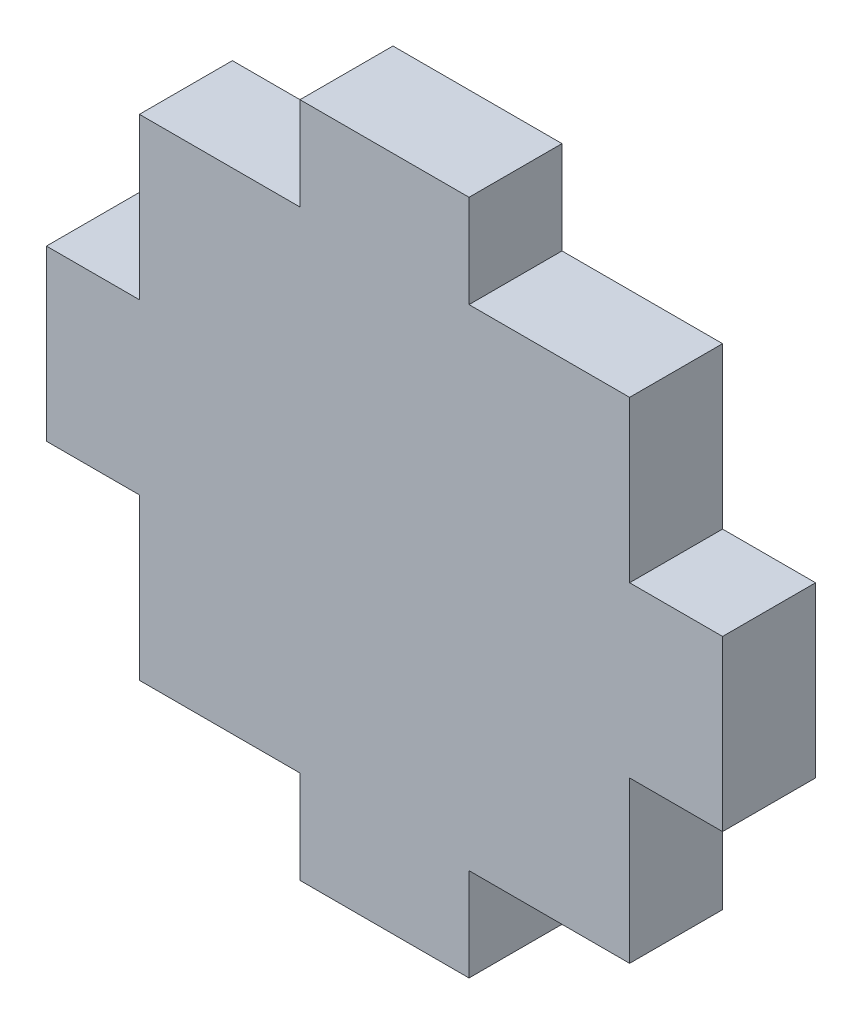
SolidWorks part; units mm, degrees
material "ﾁｰｸ材"
ref_plane "正面" through (0, 0, 0) normal (0, 0, 1) x (1, 0, 0)
ref_plane "平面" through (0, 0, 0) normal (0, 1, 0) x (1, 0, 0)
ref_plane "右側面" through (0, 0, 0) normal (1, 0, 0) x (0, 0, -1)
sketch "ｽｹｯﾁ1" plane through (0, 0, 0) normal (0, 0, 1) x (1, 0, 0)
  line L0 (-5, 14.5) -> (-14.5, 14.5)
  line L1 (14.5, 14.5) -> (5, 14.5)
  line L2 (14.5, 14.5) -> (14.5, 5)
  line L3 (14.5, -14.5) -> (5, -14.5)
  line L4 (-14.5, 14.5) -> (-14.5, 5)
  line L5 (14.5, 14.5) -> (-14.5, -14.5) construction
  line L6 (14.5, -14.5) -> (-14.5, 14.5) construction
  line L7 (-5, 20) -> (5, 20)
  line L8 (-5, 20) -> (-5, 14.5)
  line L10 (5, 20) -> (5, 14.5)
  line L11 (-5, 20) -> (5, 14.5) construction
  line L12 (-5, 14.5) -> (5, 20) construction
  line L13 (-20, 5) -> (-14.5, 5)
  line L14 (-20, 5) -> (-20, -5)
  line L15 (-20, -5) -> (-14.5, -5)
  line L17 (-20, 5) -> (-14.5, -5) construction
  line L18 (-20, -5) -> (-14.5, 5) construction
  line L19 (-5, -20) -> (5, -20)
  line L20 (-5, -20) -> (-5, -14.5)
  line L22 (5, -20) -> (5, -14.5)
  line L23 (-5, -20) -> (5, -14.5) construction
  line L24 (-5, -14.5) -> (5, -20) construction
  line L25 (20, 5) -> (14.5, 5)
  line L26 (20, 5) -> (20, -5)
  line L27 (20, -5) -> (14.5, -5)
  line L29 (20, 5) -> (14.5, -5) construction
  line L30 (20, -5) -> (14.5, 5) construction
  line L31 (-14.5, -5) -> (-14.5, -14.5)
  line L32 (-5, -14.5) -> (-14.5, -14.5)
  line L33 (14.5, -5) -> (14.5, -14.5)
  point P0 (0, 0)
  point P5 (0, 17.25)
  point P11 (-17.25, 0)
  point P16 (0, -17.25)
  point P21 (17.25, 0)
  dimension "D1" = 29
  dimension "D2" = 29
  dimension "D3" = 10
  dimension "D4" = 5.5
extrude "ﾎﾞｽ - 押し出し1" add sketch "ｽｹｯﾁ1" along normal blind 5.5
